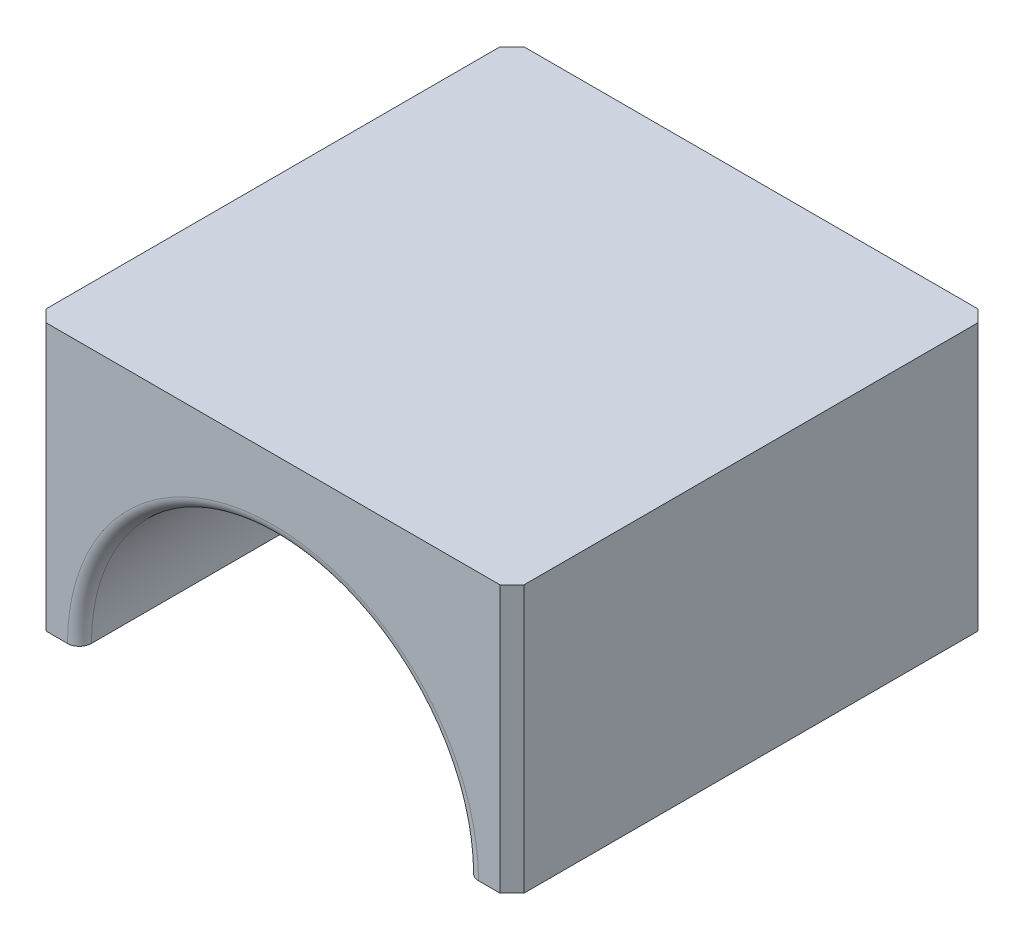
SolidWorks part; units mm, degrees
ref_plane "前视基准面" through (0, 0, 0) normal (0, 0, 1) x (1, 0, 0)
ref_plane "上视基准面" through (0, 0, 0) normal (0, 1, 0) x (1, 0, 0)
ref_plane "右视基准面" through (0, 0, 0) normal (1, 0, 0) x (0, 0, -1)
sketch "草图1" plane through (0, 0, 0) normal (0, 0, 1) x (1, 0, 0)
  line L0 (-10, -1.5875) -> (-10, -9.5875)
  line L1 (-10, 1.5875) -> (10, 1.5875)
  line L2 (-10, 1.5875) -> (-10, -1.5875)
  line L4 (10, 1.5875) -> (10, -1.5875)
  line L5 (-10, 1.5875) -> (10, -1.5875) construction
  line L6 (-10, -1.5875) -> (10, 1.5875) construction
  line L7 (-10, -9.5875) -> (-8.1, -9.5875)
  line L8 (10, -9.5875) -> (10, -1.5875)
  line L9 (8.1, -9.5875) -> (10, -9.5875)
  arc A0 (8.1, -9.5875) -> (-8.1, -9.5875) centre (0, -9.5875) ccw
  point P0 (0, 0)
extrude "凸台-拉伸1" add sketch "草图1" along normal blind 20
fillet "圆角1" radius 0.5 2 edges at (0, -1.4875, 0) (0, -1.4875, 20)
chamfer "倒角1" distance 0.5 angle 45 4 edges at (-10, -4, 20) (-10, -4, 0) (10, -4, 20) (10, -4, 0)
